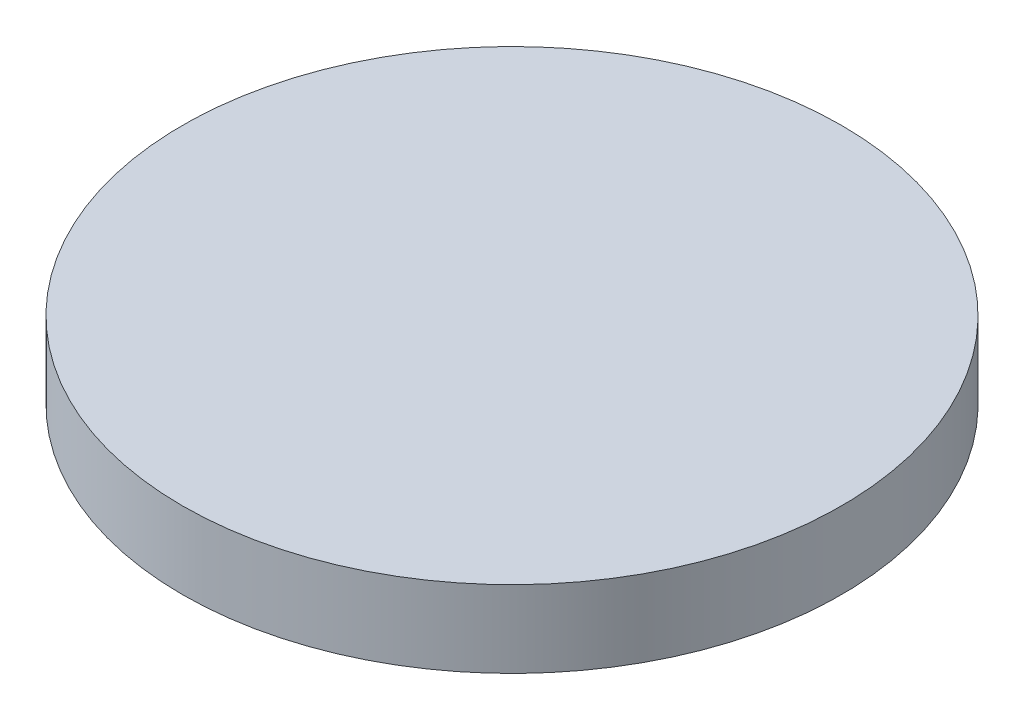
SolidWorks part; units mm, degrees
ref_plane "Alzado" through (0, 0, 0) normal (0, 0, 1) x (1, 0, 0)
ref_plane "Planta" through (0, 0, 0) normal (0, 1, 0) x (1, 0, 0)
ref_plane "Vista lateral" through (0, 0, 0) normal (1, 0, 0) x (0, 0, -1)
ref_plane "Plano_DiscoVinilo" through (0, 18, 0) normal (0, 1, 0) x (1, 0, 0)
sketch "SkDiscoVinilo" plane through (0, 18, 0) normal (0, 1, 0) x (1, 0, 0)
  circle A0 centre (0, 0) radius 60
extrude "DiscoVinilo" add sketch "SkDiscoVinilo" along normal blind 14 separate body
